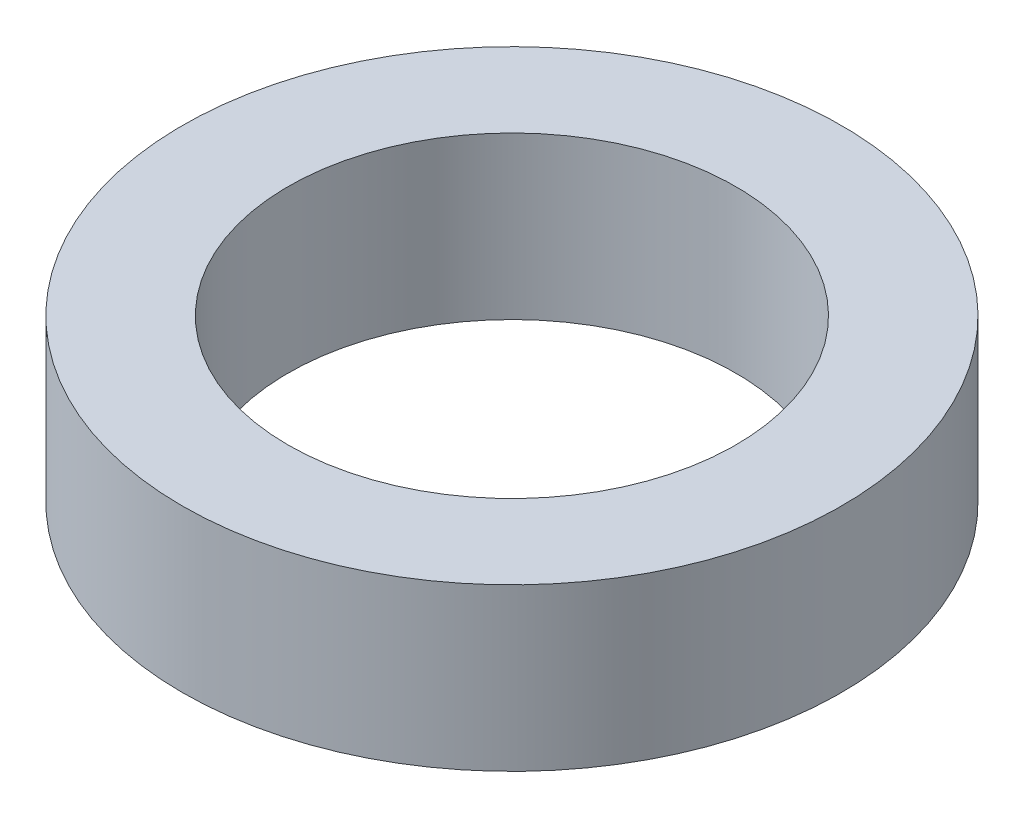
SolidWorks part; units mm, degrees
ref_plane "Front Plane" through (0, 0, 0) normal (0, 0, 1) x (1, 0, 0)
ref_plane "Top Plane" through (0, 0, 0) normal (0, 1, 0) x (1, 0, 0)
ref_plane "Right Plane" through (0, 0, 0) normal (1, 0, 0) x (0, 0, -1)
sketch "Sketch1" plane through (0, 0, 0) normal (0, 1, 0) x (1, 0, 0)
  circle A0 centre (0, 0) radius 6.731
  circle A1 centre (0, 0) radius 4.572
  dimension "D1" = 13.462
  dimension "D2" = 9.144
extrude "Boss-Extrude1" add sketch "Sketch1" along normal blind 3.3
